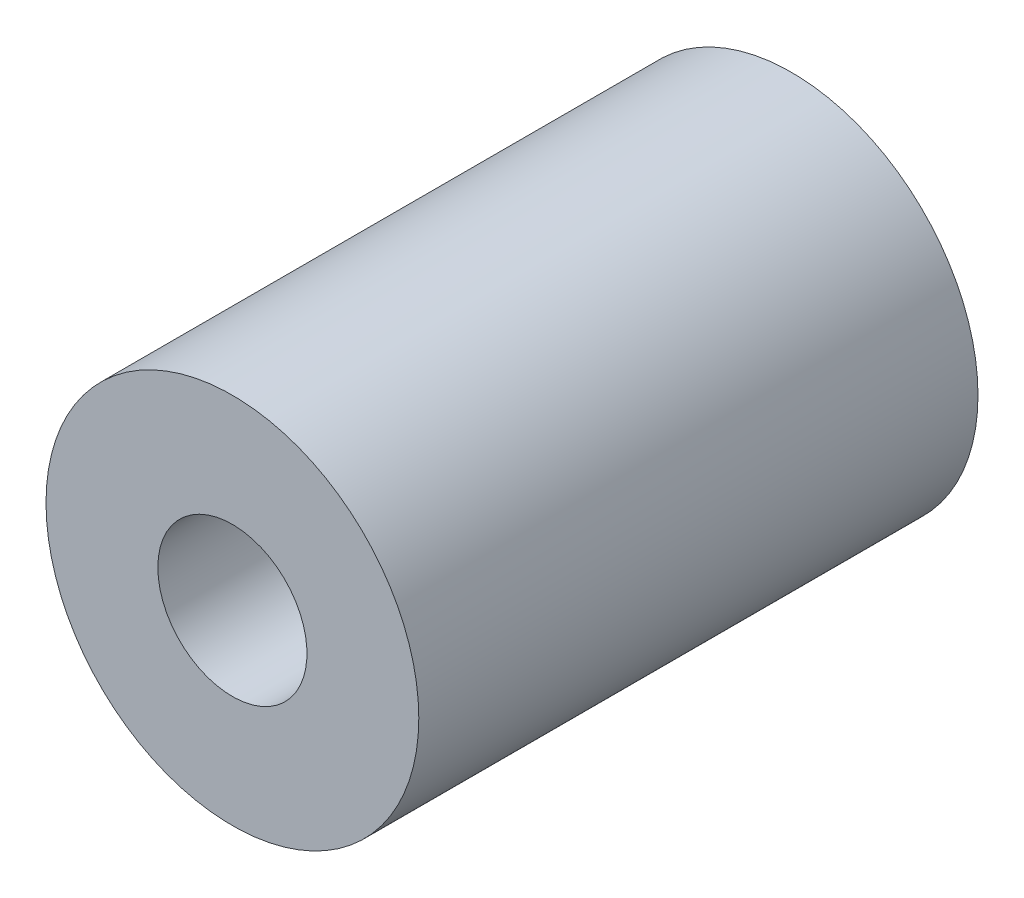
SolidWorks part; units mm, degrees
material "Alliage 1060"
ref_plane "Front Plane" through (0, 0, 0) normal (0, 0, 1) x (1, 0, 0)
ref_plane "Top Plane" through (0, 0, 0) normal (0, 1, 0) x (1, 0, 0)
ref_plane "Right Plane" through (0, 0, 0) normal (1, 0, 0) x (0, 0, -1)
sketch "Sketch1" plane through (0, 0, 0) normal (0, 0, 1) x (1, 0, 0)
  circle A0 centre (0, 0) radius 10
  circle A1 centre (0, 0) radius 4
  dimension "D1" = 20
  dimension "D2" = 8
extrude "Boss-Extrude1" add sketch "Sketch1" along normal blind 30
